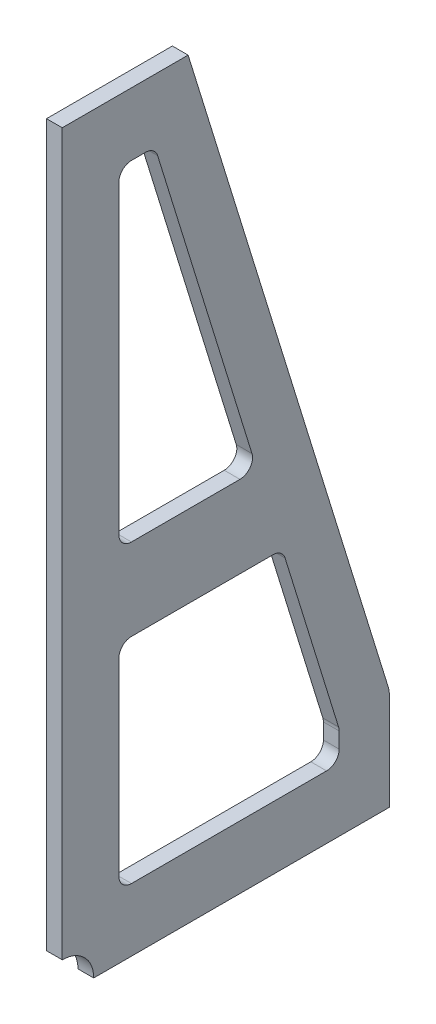
SolidWorks part; units mm, degrees
material "1.0553 (S355J0)"
ref_plane "Front Plane" through (0, 0, 0) normal (0, 0, 1) x (1, 0, 0)
ref_plane "Top Plane" through (0, 0, 0) normal (0, 1, 0) x (1, 0, 0)
ref_plane "Right Plane" through (0, 0, 0) normal (1, 0, 0) x (0, 0, -1)
sketch "Sketch1" plane through (0, 0, 0) normal (1, 0, 0) x (0, 0, -1)
  line L0 (0, 50) -> (0, 1195)
  line L1 (0, 1195) -> (200, 1195)
  line L2 (200, 1195) -> (517.7689, 167.2161)
  line L3 (520, 152.4469) -> (520, 0)
  line L4 (520, 0) -> (50, 0)
  arc A0 (50, 0) -> (0, 50) centre (0, 0) ccw
  arc A1 (517.7689, 167.2161) -> (520, 152.4469) centre (470, 152.4469) cw
  point P13 (520, 160)
  dimension "D1" = 100
  dimension "D6" = 50
  dimension "D2" = 1195
  dimension "D3" = 520
  dimension "D4" = 200
  dimension "D5" = 160
extrude "Boss-Extrude1" add sketch "Sketch1" against normal blind 25
sketch "Sketch2" plane through (0, 0, 0) normal (1, 0, 0) x (0, 0, -1)
  line L0 (90, 120) -> (90, 420)
  line L1 (110, 440) -> (334.943, 440)
  line L2 (354.0506, 425.9077) -> (439.1076, 150.8015)
  line L3 (440, 144.8938) -> (440, 120)
  line L4 (420, 100) -> (110, 100)
  line L5 (0, 1195) -> (0, 50) construction
  line L6 (50, 0) -> (520, 0) construction
  line L7 (520, 0) -> (520, 152.4469) construction
  line L8 (517.7689, 167.2161) -> (200, 1195) construction
  line L9 (90, 590) -> (90, 1075)
  line L10 (110, 1095) -> (132.4309, 1095)
  line L11 (151.5385, 1080.9077) -> (301.4902, 595.9077)
  line L12 (282.3826, 570) -> (110, 570)
  line L13 (200, 1195) -> (0, 1195) construction
  arc A0 (439.1076, 150.8015) -> (440, 144.8938) centre (420, 144.8938) cw
  arc A1 (90, 120) -> (110, 100) centre (110, 120) ccw
  arc A2 (440, 120) -> (420, 100) centre (420, 120) cw
  arc A3 (334.943, 440) -> (354.0506, 425.9077) centre (334.943, 420) cw
  arc A4 (90, 420) -> (110, 440) centre (110, 420) cw
  arc A5 (90, 1075) -> (110, 1095) centre (110, 1075) cw
  arc A6 (132.4309, 1095) -> (151.5385, 1080.9077) centre (132.4309, 1075) cw
  arc A7 (301.4902, 595.9077) -> (282.3826, 570) centre (282.3826, 590) cw
  arc A8 (90, 590) -> (110, 570) centre (110, 590) ccw
  dimension "D6" = 20
  dimension "D9" = 20
  dimension "D1" = 90
  dimension "D2" = 100
  dimension "D3" = 80
  dimension "D4" = 80
  dimension "D5" = 340
  dimension "D7" = 130
  dimension "D8" = 100
extrude "Cut-Extrude1" cut sketch "Sketch2" against normal up to next
sketch "Sketch3" plane through (0, 0, 0) normal (1, 0, 0) x (0, 0, -1)
  line L0 (0, 490) -> (559.735, 490) construction
  line L1 (50, 0) -> (520, 0) construction
  line L2 (0, 515) -> (559.735, 515) construction
  line L3 (517.7689, 167.2161) -> (200, 1195) construction
  line L4 (417.971, 490) -> (410.2415, 515) construction
  line L5 (410.2415, 515) -> (410.2415, 490) construction
  line L6 (0, 1195) -> (0, 50) construction
  dimension "D1" = 490
  dimension "D3" = 410.2415
  dimension "D2" = 25
